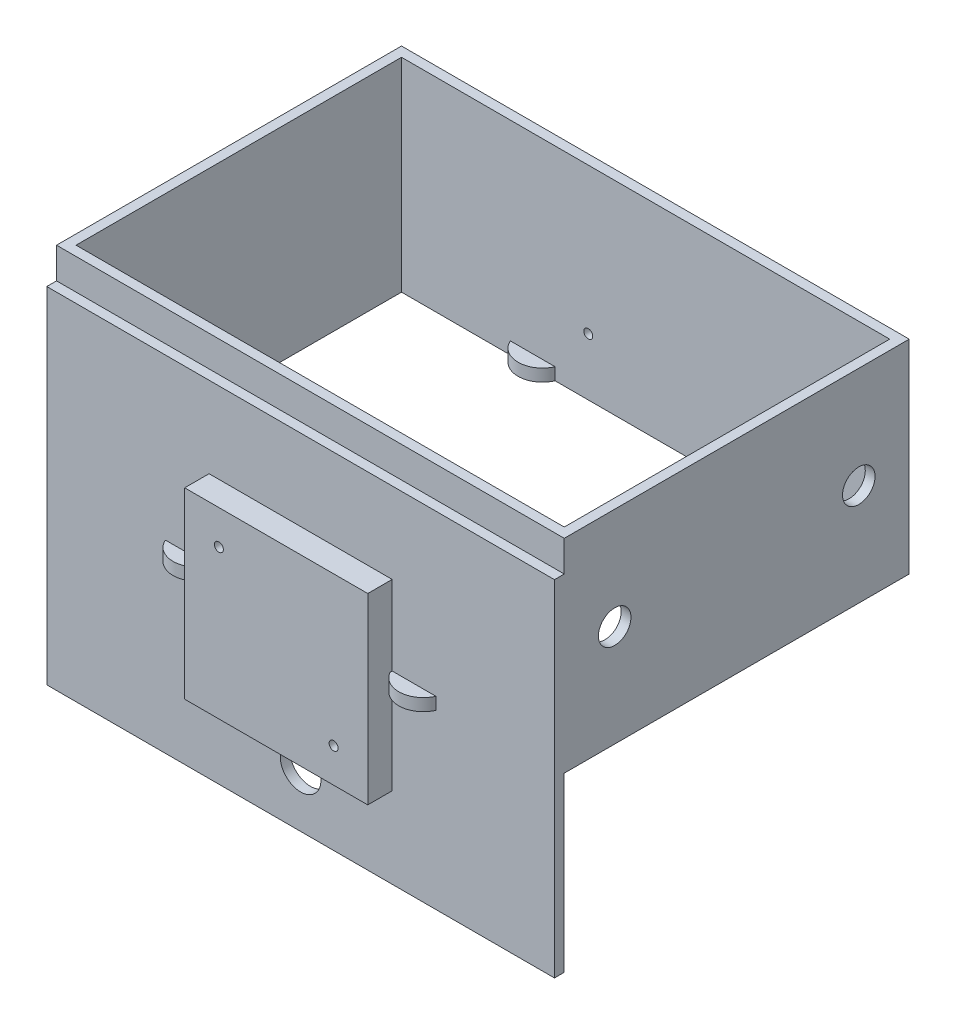
SolidWorks part; units mm, degrees
ref_plane "Front Plane" through (0, 0, 0) normal (0, 0, 1) x (1, 0, 0)
ref_plane "Top Plane" through (0, 0, 0) normal (0, 1, 0) x (1, 0, 0)
ref_plane "Right Plane" through (0, 0, 0) normal (1, 0, 0) x (0, 0, -1)
sketch "Sketch1" plane through (0, 0, 0) normal (0, 1, 0) x (1, 0, 0)
  line L1 (-62.4, -42.4) -> (62.4, -42.4)
  line L2 (-62.4, -42.4) -> (-62.4, 42.4)
  line L3 (-62.4, 42.4) -> (62.4, 42.4)
  line L4 (62.4, -42.4) -> (62.4, 42.4)
  line L5 (-60, -40) -> (60, -40)
  line L6 (-60, -40) -> (-60, 40)
  line L7 (-60, 40) -> (60, 40)
  line L8 (60, -40) -> (60, 40)
extrude "Boss-Extrude1" add sketch "Sketch1" along normal blind 50
sketch "Sketch2" plane through (0, 0, 42.4) normal (0, 0, 1) x (1, 0, 0)
  line L0 (62.4, 50) -> (62.4, 0) construction
  line L1 (-62.4, -42.4) -> (62.4, -42.4)
  line L2 (-62.4, -42.4) -> (-62.4, 42.4)
  line L3 (-62.4, 42.4) -> (62.4, 42.4)
  line L4 (62.4, -42.4) -> (62.4, 42.4)
extrude "Boss-Extrude2" add sketch "Sketch2" along normal blind 2.4
sketch "Sketch3" plane through (0, 0, 44.8) normal (0, 0, 1) x (1, 0, 0)
  line L1 (-22.5, -22.5) -> (22.5, -22.5)
  line L2 (-22.5, -22.5) -> (-22.5, 22.5)
  line L3 (-22.5, 22.5) -> (22.5, 22.5)
  line L4 (22.5, -22.5) -> (22.5, 22.5)
extrude "Boss-Extrude3" add sketch "Sketch3" along normal blind 6
sketch "Sketch4" plane through (0, 0, 50.8) normal (0, 0, 1) x (1, 0, 0)
  circle A0 centre (-14.1, 14.1) radius 1.1
  circle A1 centre (14.1, -14.1) radius 1.1
  circle A2 centre (0, -29) radius 5
extrude "Cut-Extrude1" cut sketch "Sketch4" against normal through all
sketch "Sketch5" plane through (62.4, 0, 0) normal (1, 0, 0) x (0, 0, -1)
  circle A0 centre (-30, 25) radius 4
  circle A1 centre (30, 25) radius 4
extrude "Cut-Extrude2" cut sketch "Sketch5" against normal blind 3
sketch "Sketch6" plane through (0, 0, 0) normal (0, 1, 0) x (1, 0, 0)
  line L0 (62.4, -42.4) -> (-62.4, -42.4) construction
  line L1 (62.4, 42.4) -> (-62.4, 42.4) construction
  circle A0 centre (-27.75, -42.4) radius 6
  circle A1 centre (27.75, -42.4) radius 6
  circle A2 centre (-27.75, 42.4) radius 6
  circle A3 centre (27.75, 42.4) radius 6
extrude "Boss-Extrude4" add sketch "Sketch6" along normal blind 3
